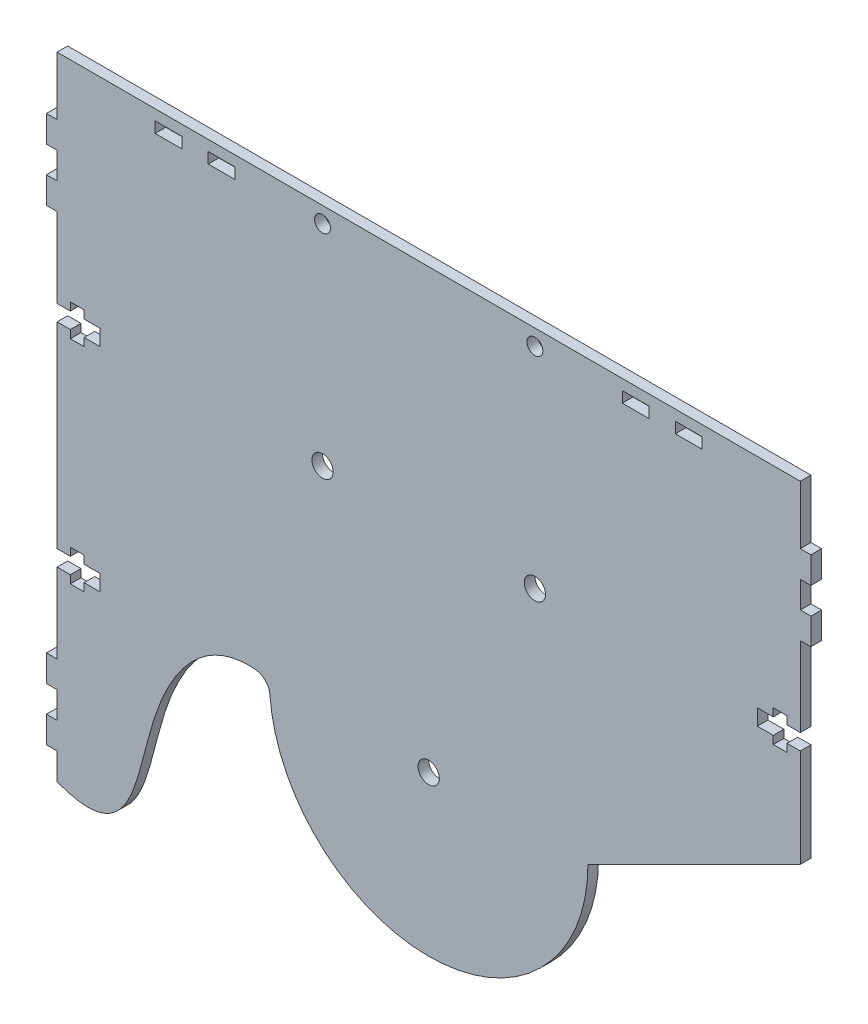
SolidWorks part; units mm, degrees
ref_plane "前视基准面" through (0, 0, 0) normal (0, 0, 1) x (1, 0, 0)
ref_plane "上视基准面" through (0, 0, 0) normal (0, 1, 0) x (1, 0, 0)
ref_plane "右视基准面" through (0, 0, 0) normal (1, 0, 0) x (0, 0, -1)
sketch "草图1" plane through (0, 0, 0) normal (0, 0, 1) x (1, 0, 0)
  line L50 (249.9534, 275.9629) -> (249.9534, 255.9629) construction
  line L73 (311.8534, 295.9629) -> (319.9534, 295.9629) construction
  line L75 (317.4534, 294.4629) -> (319.9534, 294.4629)
  line L76 (317.4534, 298.9629) -> (314.8534, 298.9629)
  line L77 (314.8534, 298.9629) -> (314.8534, 297.4629)
  line L78 (314.8534, 297.4629) -> (311.8534, 297.4629)
  line L79 (311.8534, 297.4629) -> (311.8534, 294.4629)
  line L80 (314.8534, 294.4629) -> (311.8534, 294.4629)
  line L81 (314.8534, 292.9629) -> (314.8534, 294.4629)
  line L82 (317.4534, 292.9629) -> (314.8534, 292.9629)
  line L83 (319.9534, 297.4629) -> (317.4534, 297.4629)
  line L84 (317.4534, 297.4629) -> (317.4534, 298.9629)
  line L85 (317.4534, 294.4629) -> (317.4534, 292.9629)
  line L111 (182.4534, 294.4629) -> (182.4534, 292.9629)
  line L112 (182.4534, 297.4629) -> (182.4534, 298.9629)
  line L113 (179.9534, 297.4629) -> (182.4534, 297.4629)
  line L114 (182.4534, 292.9629) -> (185.0534, 292.9629)
  line L115 (185.0534, 292.9629) -> (185.0534, 294.4629)
  line L116 (185.0534, 294.4629) -> (188.0534, 294.4629)
  line L117 (188.0534, 297.4629) -> (188.0534, 294.4629)
  line L118 (185.0534, 297.4629) -> (188.0534, 297.4629)
  line L119 (185.0534, 298.9629) -> (185.0534, 297.4629)
  line L120 (182.4534, 298.9629) -> (185.0534, 298.9629)
  line L121 (182.4534, 294.4629) -> (179.9534, 294.4629)
  line L122 (182.4534, 257.4629) -> (179.9534, 257.4629)
  line L123 (182.4534, 252.9629) -> (185.0534, 252.9629)
  line L124 (185.0534, 252.9629) -> (185.0534, 254.4629)
  line L125 (185.0534, 254.4629) -> (188.0534, 254.4629)
  line L126 (188.0534, 254.4629) -> (188.0534, 257.4629)
  line L127 (185.0534, 257.4629) -> (188.0534, 257.4629)
  line L128 (185.0534, 258.9629) -> (185.0534, 257.4629)
  line L129 (182.4534, 258.9629) -> (185.0534, 258.9629)
  line L130 (179.9534, 254.4629) -> (182.4534, 254.4629)
  line L131 (182.4534, 254.4629) -> (182.4534, 252.9629)
  line L132 (182.4534, 257.4629) -> (182.4534, 258.9629)
  line L133 (179.9534, 297.4629) -> (179.9534, 294.4629) construction
  line L134 (188.0534, 295.9629) -> (179.9534, 295.9629) construction
  line L135 (188.0534, 255.9629) -> (179.9534, 255.9629) construction
  line L163 (179.9534, 294.4629) -> (179.9534, 257.4629)
  line L188 (179.9534, 239.4629) -> (177.9534, 239.4629)
  line L189 (177.9534, 239.4629) -> (177.9534, 234.4629)
  line L190 (177.9534, 234.4629) -> (179.9534, 234.4629)
  line L191 (179.9534, 234.4629) -> (179.9534, 229.4629)
  line L192 (179.9534, 229.4629) -> (177.9534, 229.4629)
  line L193 (177.9534, 229.4629) -> (177.9534, 224.4629)
  line L194 (177.9534, 224.4629) -> (179.9534, 224.4629)
  line L196 (179.9534, 327.4629) -> (179.9534, 345.9629) construction
  line L197 (177.9534, 327.4629) -> (179.9534, 327.4629)
  line L198 (177.9534, 322.4629) -> (177.9534, 327.4629)
  line L199 (179.9534, 322.4629) -> (177.9534, 322.4629)
  line L200 (179.9534, 317.4629) -> (179.9534, 322.4629)
  line L201 (177.9534, 317.4629) -> (179.9534, 317.4629)
  line L202 (177.9534, 312.4629) -> (177.9534, 317.4629)
  line L203 (179.9534, 312.4629) -> (177.9534, 312.4629)
  line L224 (319.9534, 312.4629) -> (321.9534, 312.4629)
  line L225 (321.9534, 312.4629) -> (321.9534, 317.4629)
  line L226 (321.9534, 317.4629) -> (319.9534, 317.4629)
  line L227 (319.9534, 317.4629) -> (319.9534, 322.4629)
  line L228 (319.9534, 322.4629) -> (321.9534, 322.4629)
  line L229 (321.9534, 322.4629) -> (321.9534, 327.4629)
  line L230 (321.9534, 327.4629) -> (319.9534, 327.4629)
  line L231 (319.9534, 327.4629) -> (319.9534, 345.9629) construction
  line L261 (249.9534, 255.9629) -> (229.9534, 255.9629) construction
  line L262 (229.9534, 335.4629) -> (269.9534, 335.4629) construction
  line L263 (249.9534, 335.4629) -> (249.9534, 338.4629) construction
  line L268 (179.9534, 297.4629) -> (179.9534, 312.4629)
  line L271 (319.9534, 312.4629) -> (319.9534, 297.4629)
  line L275 (179.9534, 239.4629) -> (179.9534, 254.4629)
  line L279 (319.9534, 338.4629) -> (179.9534, 338.4629)
  line L280 (179.9534, 327.4629) -> (179.9534, 338.4629)
  line L285 (319.9534, 338.4629) -> (319.9534, 327.4629)
  line L288 (179.9534, 224.4629) -> (179.9534, 219.4131)
  line L292 (319.9534, 275.9629) -> (319.9534, 294.4629)
  line L293 (279.9534, 255.9629) -> (319.9534, 275.9629)
  line L309 (179.9534, 345.9629) -> (319.9534, 345.9629) construction
  line L310 (203.4784, 334.4379) -> (198.4284, 336.4879) construction
  line L311 (286.4284, 336.4879) -> (291.4784, 336.4879)
  line L312 (286.4284, 336.4879) -> (286.4284, 334.4379)
  line L313 (286.4284, 334.4379) -> (291.4784, 334.4379)
  line L314 (291.4784, 336.4879) -> (291.4784, 334.4379)
  line L315 (286.4284, 336.4879) -> (291.4784, 334.4379) construction
  line L316 (286.4284, 334.4379) -> (291.4784, 336.4879) construction
  line L317 (296.4284, 336.4879) -> (301.4784, 336.4879)
  line L318 (296.4284, 336.4879) -> (296.4284, 334.4379)
  line L319 (296.4284, 334.4379) -> (301.4784, 334.4379)
  line L320 (301.4784, 336.4879) -> (301.4784, 334.4379)
  line L321 (296.4284, 336.4879) -> (301.4784, 334.4379) construction
  line L322 (296.4284, 334.4379) -> (301.4784, 336.4879) construction
  line L333 (231.4534, 343.4629) -> (231.4534, 345.9629) [skipped]
  line L334 (226.9534, 343.4629) -> (226.9534, 340.8629) [skipped]
  line L335 (226.9534, 340.8629) -> (228.4534, 340.8629) [skipped]
  line L336 (228.4534, 340.8629) -> (228.4534, 337.8629) [skipped]
  line L337 (231.4534, 340.8629) -> (231.4534, 337.8629) [skipped]
  line L338 (232.9534, 340.8629) -> (231.4534, 340.8629) [skipped]
  line L339 (232.9534, 343.4629) -> (232.9534, 340.8629) [skipped]
  line L340 (228.4534, 345.9629) -> (228.4534, 343.4629) [skipped]
  line L341 (228.4534, 343.4629) -> (226.9534, 343.4629) [skipped]
  line L342 (231.4534, 343.4629) -> (232.9534, 343.4629) [skipped]
  line L344 (213.4534, 345.9629) -> (213.4534, 347.9629) [skipped]
  line L345 (213.4534, 347.9629) -> (208.4534, 347.9629) [skipped]
  line L346 (208.4534, 347.9629) -> (208.4534, 345.9629) [skipped]
  line L347 (208.4534, 345.9629) -> (203.4534, 345.9629) [skipped]
  line L348 (203.4534, 345.9629) -> (203.4534, 347.9629) [skipped]
  line L349 (203.4534, 347.9629) -> (198.4534, 347.9629) [skipped]
  line L350 (198.4534, 347.9629) -> (198.4534, 345.9629) [skipped]
  line L352 (301.4534, 345.9629) -> (319.9534, 345.9629) [skipped]
  line L353 (301.4534, 347.9629) -> (301.4534, 345.9629) [skipped]
  line L354 (296.4534, 347.9629) -> (301.4534, 347.9629) [skipped]
  line L355 (296.4534, 345.9629) -> (296.4534, 347.9629) [skipped]
  line L356 (291.4534, 345.9629) -> (296.4534, 345.9629) [skipped]
  line L357 (291.4534, 347.9629) -> (291.4534, 345.9629) [skipped]
  line L358 (286.4534, 347.9629) -> (291.4534, 347.9629) [skipped]
  line L359 (286.4534, 345.9629) -> (286.4534, 347.9629) [skipped]
  line L362 (229.9534, 337.8629) -> (229.9534, 345.9629) construction
  line L364 (228.4534, 337.8629) -> (231.4534, 337.8629) [skipped]
  line L365 (203.4784, 336.4879) -> (198.4284, 334.4379) construction
  line L366 (213.4784, 334.4379) -> (208.4284, 336.4879) construction
  line L367 (213.4784, 336.4879) -> (208.4284, 334.4379) construction
  line L368 (198.4284, 336.4879) -> (198.4284, 334.4379)
  line L369 (203.4784, 334.4379) -> (198.4284, 334.4379)
  line L370 (203.4784, 336.4879) -> (203.4784, 334.4379)
  line L371 (203.4784, 336.4879) -> (198.4284, 336.4879)
  line L372 (208.4284, 336.4879) -> (208.4284, 334.4379)
  line L373 (213.4784, 334.4379) -> (208.4284, 334.4379)
  line L374 (213.4784, 336.4879) -> (213.4784, 334.4379)
  line L375 (213.4784, 336.4879) -> (208.4284, 336.4879)
  line L387 (268.4534, 208.4629) -> (268.4534, 205.9629) [skipped]
  line L388 (272.9534, 208.4629) -> (272.9534, 211.0629) [skipped]
  line L389 (272.9534, 211.0629) -> (271.4534, 211.0629) [skipped]
  line L390 (271.4534, 211.0629) -> (271.4534, 214.0629) [skipped]
  line L391 (271.4534, 214.0629) -> (268.4534, 214.0629) [skipped]
  line L392 (268.4534, 211.0629) -> (268.4534, 214.0629) [skipped]
  line L393 (266.9534, 211.0629) -> (268.4534, 211.0629) [skipped]
  line L394 (266.9534, 208.4629) -> (266.9534, 211.0629) [skipped]
  line L395 (271.4534, 205.9629) -> (271.4534, 208.4629) [skipped]
  line L396 (271.4534, 208.4629) -> (272.9534, 208.4629) [skipped]
  line L397 (268.4534, 208.4629) -> (266.9534, 208.4629) [skipped]
  line L399 (286.4534, 205.9629) -> (286.4534, 203.9629) [skipped]
  line L400 (286.4534, 203.9629) -> (291.4534, 203.9629) [skipped]
  line L401 (291.4534, 203.9629) -> (291.4534, 205.9629) [skipped]
  line L402 (291.4534, 205.9629) -> (296.4534, 205.9629) [skipped]
  line L403 (296.4534, 205.9629) -> (296.4534, 203.9629) [skipped]
  line L404 (296.4534, 203.9629) -> (301.4534, 203.9629) [skipped]
  line L405 (198.4534, 205.9629) -> (179.9534, 205.9629) [skipped]
  line L406 (198.4534, 203.9629) -> (198.4534, 205.9629) [skipped]
  line L407 (203.4534, 203.9629) -> (198.4534, 203.9629) [skipped]
  line L408 (203.4534, 205.9629) -> (203.4534, 203.9629) [skipped]
  line L409 (208.4534, 205.9629) -> (203.4534, 205.9629) [skipped]
  line L410 (208.4534, 203.9629) -> (208.4534, 205.9629) [skipped]
  line L411 (213.4534, 203.9629) -> (208.4534, 203.9629) [skipped]
  line L412 (213.4534, 205.9629) -> (213.4534, 203.9629) [skipped]
  line L415 (269.9534, 214.0629) -> (269.9534, 205.9629) construction
  line L416 (319.9534, 224.4629) -> (319.9534, 205.9629) [skipped]
  line L417 (301.4534, 203.9629) -> (301.4534, 205.9629) [skipped]
  line L418 (321.9534, 224.4629) -> (319.9534, 224.4629) [skipped]
  line L419 (321.9534, 229.4629) -> (321.9534, 224.4629) [skipped]
  line L420 (319.9534, 229.4629) -> (321.9534, 229.4629) [skipped]
  line L421 (319.9534, 234.4629) -> (319.9534, 229.4629) [skipped]
  line L422 (321.9534, 234.4629) -> (319.9534, 234.4629) [skipped]
  line L423 (321.9534, 239.4629) -> (321.9534, 234.4629) [skipped]
  line L424 (319.9534, 239.4629) -> (321.9534, 239.4629) [skipped]
  circle A24 centre (249.9534, 255.9629) radius 2
  circle A27 centre (229.9534, 335.4629) radius 1.5
  circle A28 centre (269.9534, 335.4629) radius 1.5
  circle A30 centre (229.9534, 295.9629) radius 2
  circle A31 centre (269.9534, 295.9629) radius 2
  circle A33 centre (249.9534, 255.9629) radius 16.5 construction
  circle A36 centre (249.9534, 255.9629) radius 30 construction
  arc A39 (279.9534, 255.9629) -> (220.0403, 253.6812) centre (249.9534, 255.9629) cw
  arc A40 (220.0403, 253.6812) -> (217.334, 256.4394) centre (217.0489, 253.453) ccw
  spline S0 degree 3 poles (217.334, 256.4394) (215.5487, 256.6099) (206.5476, 255.6614) (194.457, 237.2425) (194.6881, 213.9708) (179.9534, 219.4131) knots 0.040254 0.040254 0.040254 0.040254 0.124939 0.47726 1 1 1 1
  point P14 (198.4284, 239.4629)
  point P107 (210.9534, 335.4629)
  point P232 (288.9534, 335.4629)
  dimension "D1" = 3
  dimension "D5" = 4
extrude "凸台-拉伸1" add sketch "草图1" along normal blind 2
sketch "草图2" plane through (179.9534, 0, 0) normal (-1, 0, 0) x (0, 0, 1)
  line L0 (1, 294.4629) -> (1, 297.4629) construction
  line L1 (2, 294.4629) -> (0, 294.4629) construction
  line L2 (2, 297.4629) -> (0, 297.4629) construction
  line L3 (1, 295.9629) -> (1, 312.4629) construction
  line L4 (2, 312.4629) -> (0, 312.4629) construction
  circle A0 centre (1, 295.9629) radius 1.5
